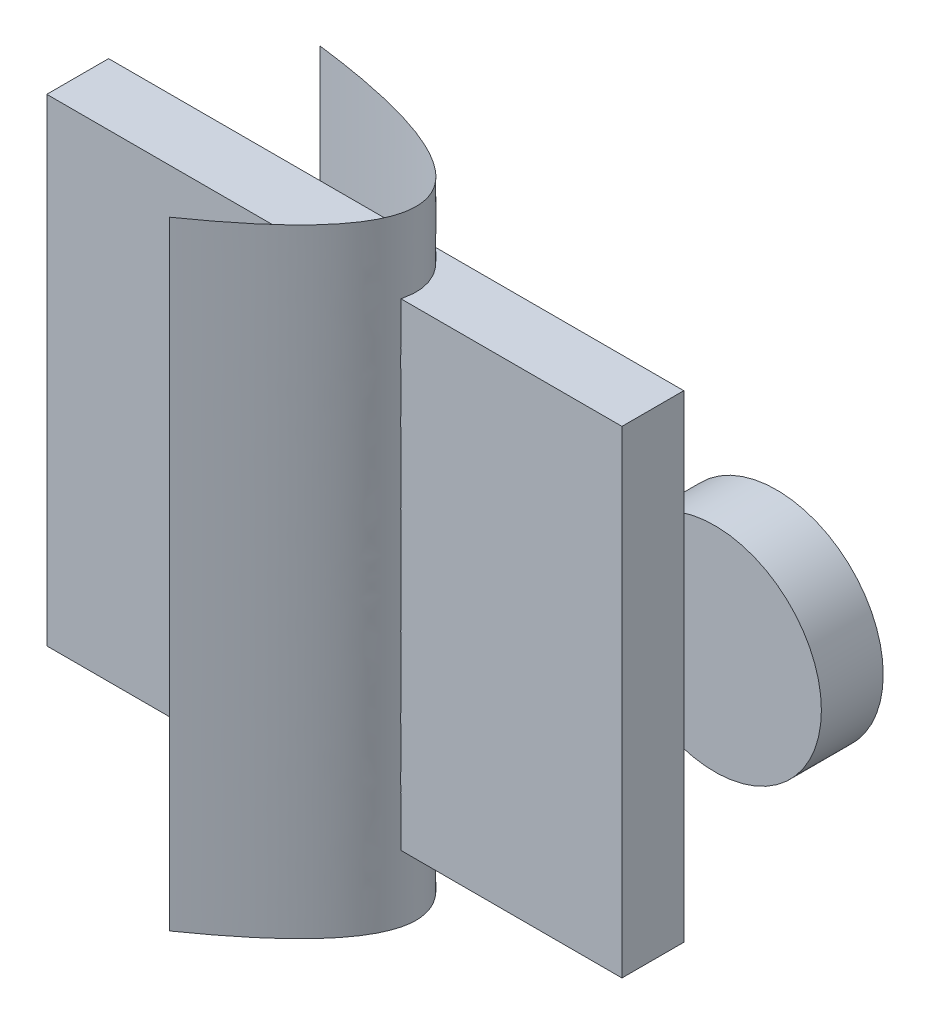
SolidWorks part; units mm, degrees
ref_plane "Спереди" through (0, 0, 0) normal (0, 0, 1) x (1, 0, 0)
ref_plane "Сверху" through (0, 0, 0) normal (0, 1, 0) x (1, 0, 0)
ref_plane "Справа" through (0, 0, 0) normal (1, 0, 0) x (0, 0, -1)
sketch "Эскиз1_fr" plane through (0, 0, 0) normal (0, 0, 1) x (1, 0, 0)
  line L1 (-48.994, 38.0205) -> (44.0482, 38.0205)
  line L2 (-48.994, 38.0205) -> (-48.994, -39.257)
  line L3 (-48.994, -39.257) -> (44.0482, -39.257)
  line L4 (44.0482, 38.0205) -> (44.0482, -39.257)
extrude "Бобышка-Вытянуть1" add sketch "Эскиз1_fr" along normal blind 10
ref_plane "Плоскость4" through (0, 0, -5) normal (0, 0, 1) x (1, 0, 0)
sketch "Эскиз5" plane through (0, 0, -5) normal (0, 0, 1) x (1, 0, 0)
  line L0 (44.0482, -39.257) -> (44.0482, 38.0205) construction
  circle A0 centre (44.0482, -0.6182) radius 17.2618
extrude "Бобышка-Вытянуть2" add sketch "Эскиз5" against normal blind 10 separate body
ref_plane "Плоскость5" through (0, 0, 20) normal (0, 0, 1) x (1, 0, 0)
sketch "Эскиз6" plane through (0, 0, 20) normal (0, 0, 1) x (1, 0, 0)
  line L0 (44.0482, -39.257) -> (44.0482, 38.0205) construction
  line L1 (50.2984, -11.4439) -> (56.5486, -0.6182)
  line L2 (56.5486, -0.6182) -> (50.2984, 10.2074)
  line L3 (50.2984, 10.2074) -> (37.798, 10.2074)
  line L4 (37.798, 10.2074) -> (31.5478, -0.6182)
  line L5 (31.5478, -0.6182) -> (37.798, -11.4439)
  line L6 (37.798, -11.4439) -> (50.2984, -11.4439)
  circle A0 centre (44.0482, -0.6182) radius 10.8257 construction
sketch "Эскиз7" plane through (0, 0, 0) normal (0, 1, 0) x (1, 0, 0)
  spline S0 degree 2 poles (-9.8895, -29.2716) (32.2081, 0.1563) (-21.677, 6.8901) knots 0 0 0 1 1 1
surface "Поверхность-Вытянуть1" sketch "Эскиз7" parameters "D1"=50, "D2"=50
